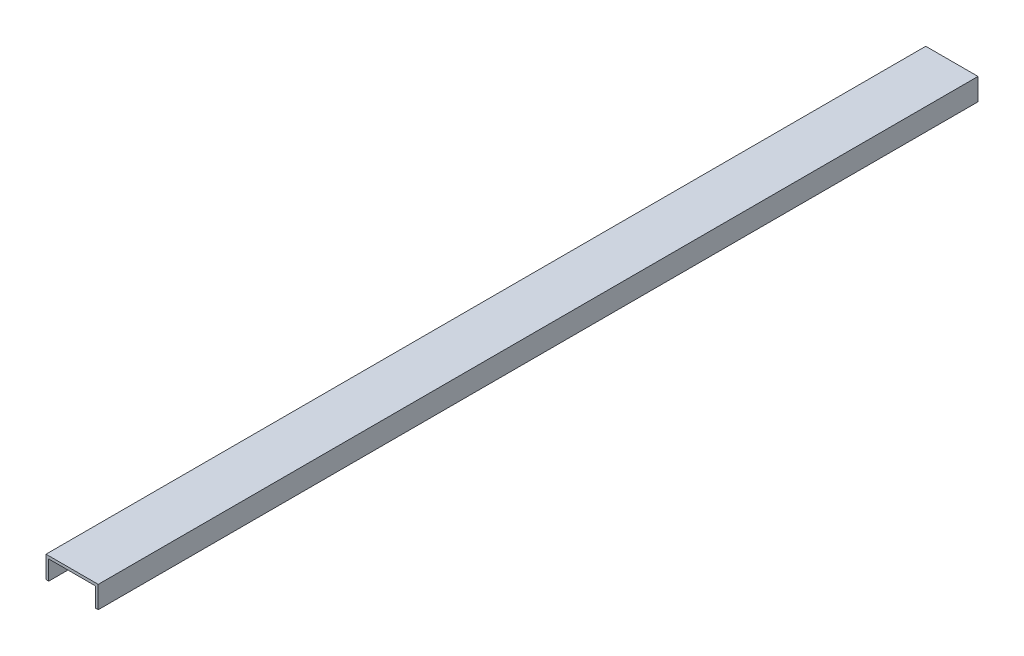
SolidWorks part; units mm, degrees
ref_plane "Front Plane" through (0, 0, 0) normal (0, 0, 1) x (1, 0, 0)
ref_plane "Top Plane" through (0, 0, 0) normal (0, 1, 0) x (1, 0, 0)
ref_plane "Right Plane" through (0, 0, 0) normal (1, 0, 0) x (0, 0, -1)
sketch "Sketch1" plane through (0, 0, 0) normal (0, 0, 1) x (1, 0, 0)
  line L0 (0, 0) -> (-8.5, 0)
  line L1 (-8.5, 0) -> (-8.5, -7)
  line L2 (0, 0) -> (8.5, 0)
  line L3 (8.5, 0) -> (8.5, -7)
  line L4 (8.5, -7) -> (9.5, -7)
  line L5 (9.5, -7) -> (9.5, 1)
  line L6 (9.5, 1) -> (-9.5, 1)
  line L7 (-9.5, 1) -> (-9.5, -7)
  line L8 (-9.5, -7) -> (-8.5, -7)
extrude "Boss-Extrude1" add sketch "Sketch1" along normal blind 320
